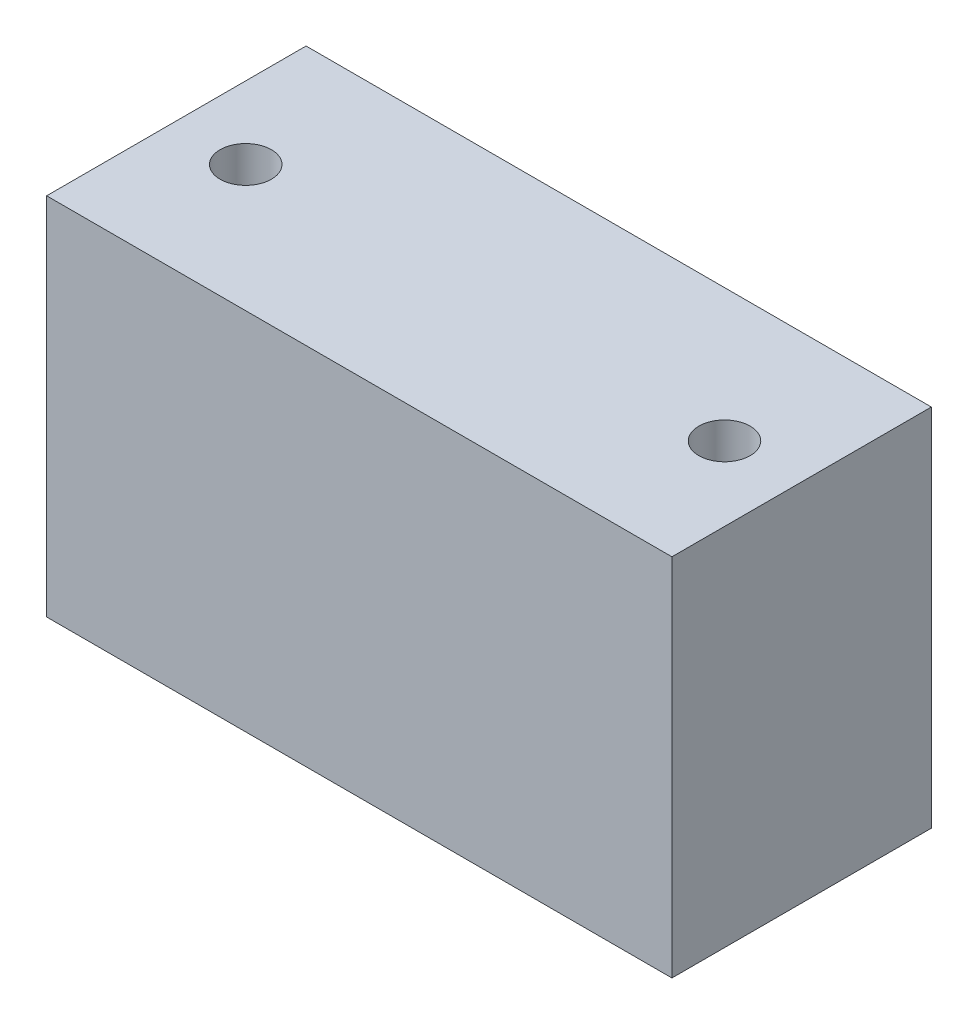
SolidWorks part; units mm, degrees
material "PET"
ref_plane "Alzado" through (0, 0, 0) normal (0, 0, 1) x (1, 0, 0)
ref_plane "Planta" through (0, 0, 0) normal (0, 1, 0) x (1, 0, 0)
ref_plane "Vista lateral" through (0, 0, 0) normal (1, 0, 0) x (0, 0, -1)
sketch "Croquis1" plane through (0, 0, 0) normal (0, 1, 0) x (1, 0, 0)
  line L1 (17.4953, -3.3538) -> (72.3484, -3.3538)
  line L2 (17.4953, -3.3538) -> (17.4953, 19.405)
  line L3 (17.4953, 19.405) -> (72.3484, 19.405)
  line L4 (72.3484, -3.3538) -> (72.3484, 19.405)
extrude "Saliente-Extruir1" add sketch "Croquis1" along normal blind 32
sketch "Croquis2" plane through (0, 32, 0) normal (0, 1, 0) x (1, 0, 0)
  line L0 (44.9219, 24.5318) -> (44.9219, -7.6041) construction
  line L1 (8.7543, 8.0256) -> (81.031, 8.0256) construction
  line L2 (17.4953, -3.3538) -> (72.3484, -3.3538) construction
  line L3 (72.3484, 19.405) -> (17.4953, 19.405) construction
  line L4 (17.4953, 19.405) -> (17.4953, -3.3538) construction
  line L5 (72.3484, -3.3538) -> (72.3484, 19.405) construction
  circle A2 centre (23.8484, 7.7574) radius 2.25
  circle A3 centre (65.8484, 7.7574) radius 2.25
extrude "Cortar-Extruir1" cut sketch "Croquis2" against normal through all
